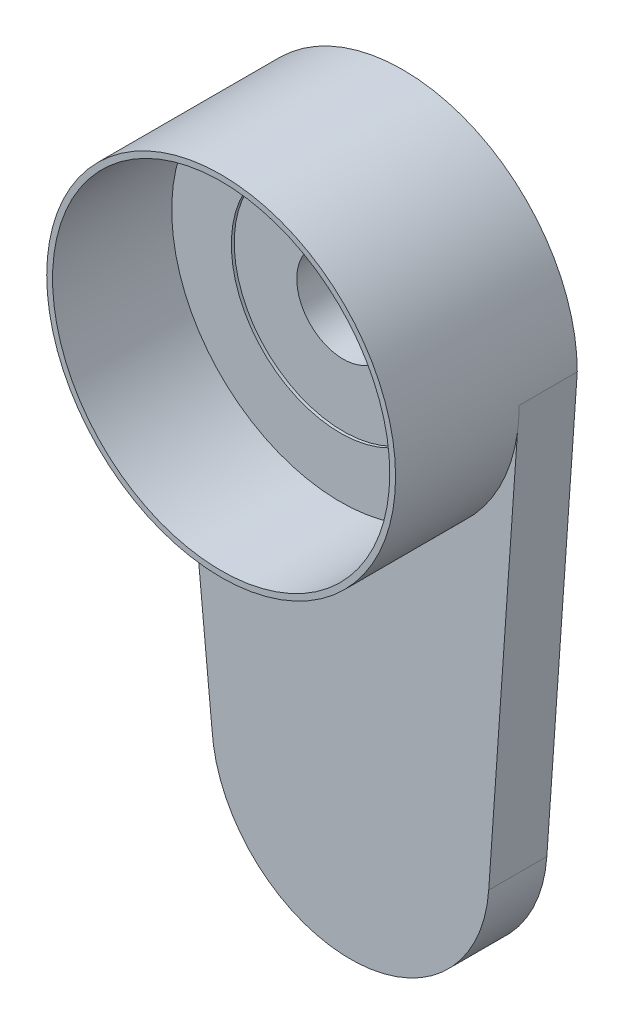
SolidWorks part; units mm, degrees
ref_plane "Front Plane" through (0, 0, 0) normal (0, 0, 1) x (1, 0, 0)
ref_plane "Top Plane" through (0, 0, 0) normal (0, 1, 0) x (1, 0, 0)
ref_plane "Right Plane" through (0, 0, 0) normal (1, 0, 0) x (0, 0, -1)
sketch "Sketch2" plane through (0, 0, 0) normal (0, 0, 1) x (1, 0, 0)
  circle A0 centre (0, 0) radius 120
extrude "Boss-Extrude2" add sketch "Sketch2" along normal blind 85
sketch "Sketch3" plane through (0, 0, 85) normal (0, 0, 1) x (1, 0, 0)
  circle A0 centre (0, 0) radius 116
extrude "Cut-Extrude1" cut sketch "Sketch3" against normal blind 82
sketch "Sketch8" plane through (0, 0, 3) normal (0, 0, 1) x (1, 0, 0)
  circle A0 centre (0, 0) radius 75
extrude "Cut-Extrude5" cut sketch "Sketch8" along normal blind 2 and the other way blind 2
sketch "Sketch9" plane through (0, 0, 1) normal (0, 0, 1) x (1, 0, 0)
  line L0 (0, 0) -> (-75, 0) construction
  line L1 (0, 0) -> (0, 75) construction
  circle A0 centre (0, 0) radius 75 construction
  circle A1 centre (0, 0) radius 32
extrude "Cut-Extrude6" cut sketch "Sketch9" against normal blind 5 contours A1
sketch "Sketch12" plane through (0, 0, 0) normal (0, 0, -1) x (-1, 0, 0)
  line L0 (-120, 0) -> (-99.0634, -299.2685)
  line L1 (120, 0) -> (91.3099, -298.625)
  circle A1 centre (0, 0) radius 120 construction
  arc A2 (-99.0634, -299.2685) -> (91.3099, -298.625) centre (-3.8981, -292.6108) ccw
  circle A3 centre (0, 0) radius 120
  circle M3 centre (0, 0) radius 32
  circle M4 centre (0, 0) radius 120
extrude "Boss-Extrude4" add sketch "Sketch12" along normal blind 40 contours L1 L0 M4 M3 | L0 A2 L1 M4
